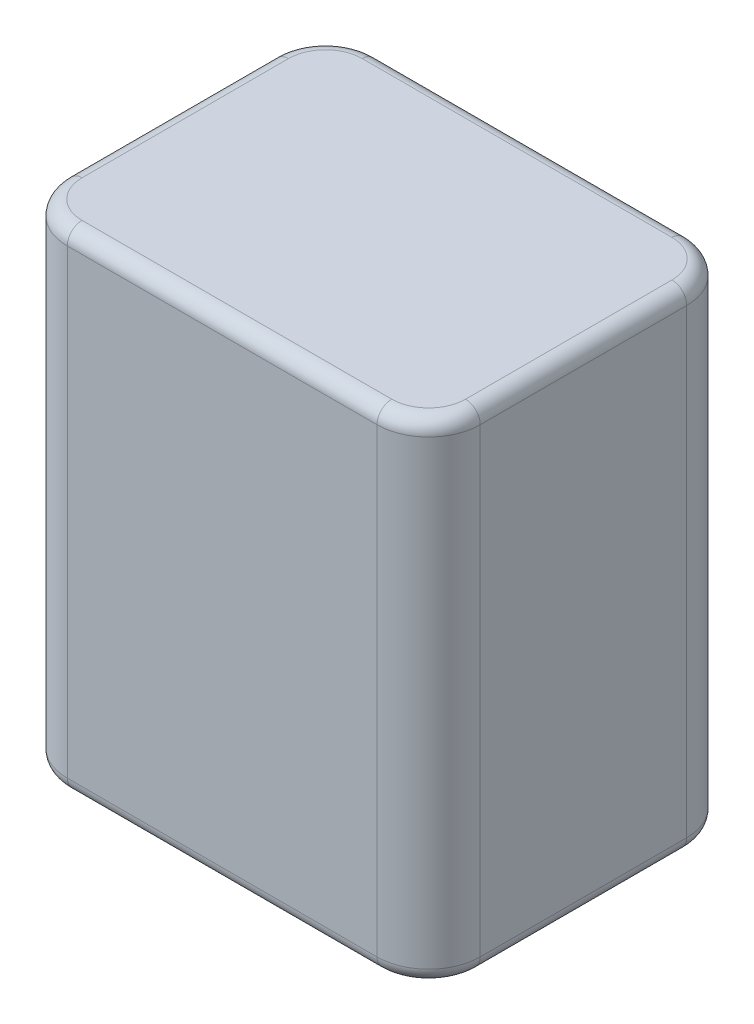
SolidWorks part; units mm, degrees
material "ABS"
ref_plane "Front Plane" through (0, 0, 0) normal (0, 0, 1) x (1, 0, 0)
ref_plane "Top Plane" through (0, 0, 0) normal (0, 1, 0) x (1, 0, 0)
ref_plane "Right Plane" through (0, 0, 0) normal (1, 0, 0) x (0, 0, -1)
sketch "Sketch1" plane through (0, 0, 0) normal (0, 1, 0) x (1, 0, 0)
  line L1 (-21, -21) -> (21, -21)
  line L2 (-28, -14) -> (-28, 14)
  line L3 (-21, 21) -> (21, 21)
  line L4 (28, -14) -> (28, 14)
  line L5 (-28, -21) -> (28, 21) construction
  line L6 (-28, 21) -> (28, -21) construction
  arc A0 (-21, -21) -> (-28, -14) centre (-21, -14) cw
  arc A1 (21, -21) -> (28, -14) centre (21, -14) ccw
  arc A2 (21, 21) -> (28, 14) centre (21, 14) cw
  arc A3 (-28, 14) -> (-21, 21) centre (-21, 14) cw
  point P0 (0, 0)
  dimension "D3" = 7
  dimension "D1" = 42
  dimension "D2" = 56
extrude "Boss-Extrude1" add sketch "Sketch1" along normal blind 66.5
fillet "Fillet1" radius 2 16 edges at (0, 0, 21) (25.9497, 0, 18.9497) (28, 0, 0) (25.9497, 0, -18.9497) (0, 0, -21) (-25.9497, 0, -18.9497) (-28, 0, 0) (-25.9497, 0, 18.9497) (-28, 66.5, 0) (-25.9497, 66.5, -18.9497) (0, 66.5, -21) (25.9497, 66.5, -18.9497) (28, 66.5, 0) (25.9497, 66.5, 18.9497) (0, 66.5, 21) (-25.9497, 66.5, 18.9497)
